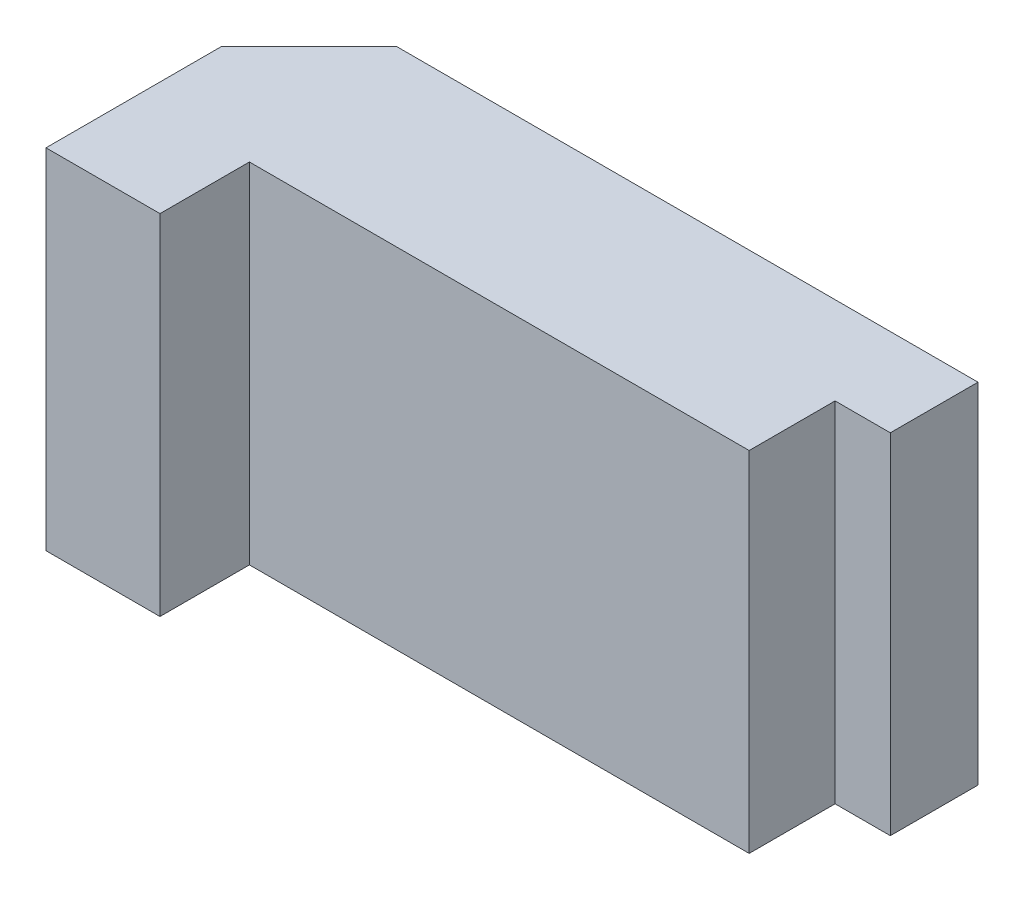
SolidWorks part; units mm, degrees
ref_plane "Front Plane" through (0, 0, 0) normal (0, 0, 1) x (1, 0, 0)
ref_plane "Top Plane" through (0, 0, 0) normal (0, 1, 0) x (1, 0, 0)
ref_plane "Right Plane" through (0, 0, 0) normal (1, 0, 0) x (0, 0, -1)
sketch "Sketch1" plane through (0, 0, 0) normal (0, 1, 0) x (1, 0, 0)
  line L0 (0, 0) -> (0, 20)
  line L1 (0, 20) -> (10, 30)
  line L2 (10, 30) -> (76.3, 30)
  line L3 (76.3, 30) -> (76.3, 20)
  line L4 (76.3, 20) -> (70, 20)
  line L5 (70, 20) -> (70, 10.2)
  line L6 (70, 10.2) -> (13, 10.2)
  line L7 (13, 10.2) -> (13, 0)
  line L8 (13, 0) -> (0, 0)
  dimension "D1" = 76.3
  dimension "D2" = 30
  dimension "D3" = 19.8
  dimension "D5" = 13
  dimension "D6" = 70
  dimension "D7" = 45
  dimension "D8" = 10
  dimension "D9" = 20
extrude "Boss-Extrude1" add sketch "Sketch1" along normal mid plane 39.8
